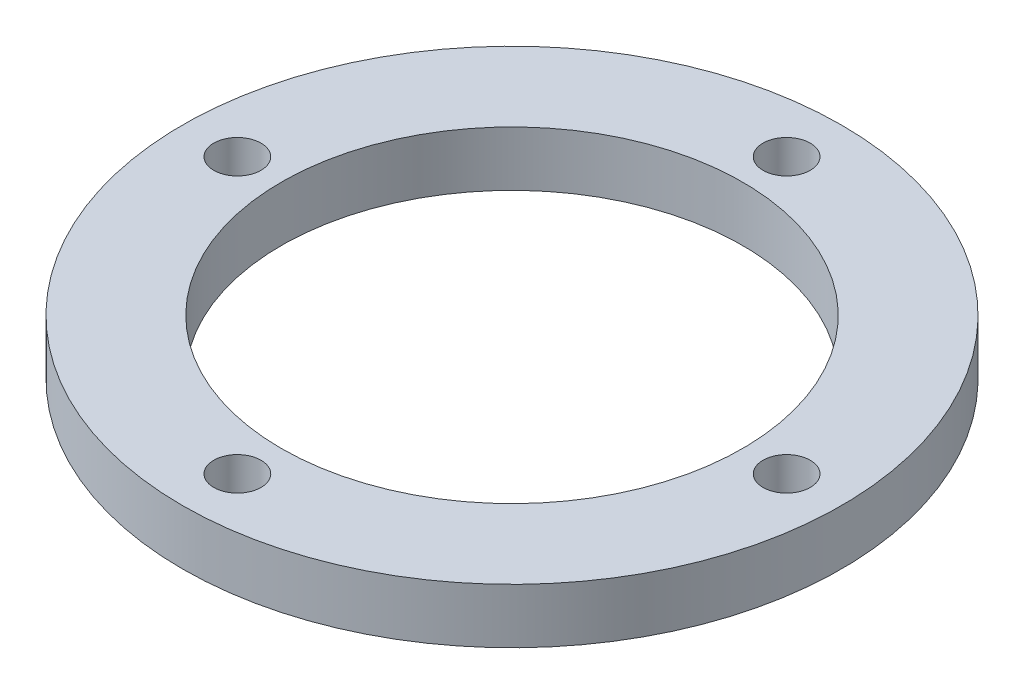
SolidWorks part; units mm, degrees
ref_plane "Front Plane" through (0, 0, 0) normal (0, 0, 1) x (1, 0, 0)
ref_plane "Top Plane" through (0, 0, 0) normal (0, 1, 0) x (1, 0, 0)
ref_plane "Right Plane" through (0, 0, 0) normal (1, 0, 0) x (0, 0, -1)
sketch "Sketch1" plane through (0, 0, 0) normal (0, 1, 0) x (1, 0, 0)
  circle A0 centre (0, 0) radius 21
  circle A1 centre (0, 0) radius 30
  dimension "D1" = 42
  dimension "D2" = 60
extrude "Boss-Extrude1" add sketch "Sketch1" along normal blind 5
hole_wizard "M4 Clearance Hole1" positions "Sketch3" profile "Sketch2" hole size "M4" standard "ISO" end condition through all
sketch "Sketch3" plane through (0, 5, 0) normal (0, 1, 0) x (1, 0, 0)
  line L0 (0, -30) -> (0, 30) construction
  line L2 (-30, 0) -> (30, 0) construction
  circle A0 centre (0, 0) radius 30 construction
  point P0 (0, -25)
  point P3 (0, 25)
  point P5 (25, 0)
  point P7 (-25, 0)
  dimension "D1" = 25
  dimension "D2" = 25
sketch "Sketch2" plane through (0, 5, 25) normal (1, 0, 0) x (0, 0, 1)
  line L0 (0, 0) -> (0, 5)
  line L1 (0, 5) -> (2.15, 5)
  line L2 (2.15, 5) -> (2.15, 0)
  line L5 (2.15, 0) -> (0, 0)
  line L11 (0, -6.35) -> (0, 107.95) construction
  dimension "Thru Hole Dia." = 4.3
  dimension "Thru Hole Depth" = 5
